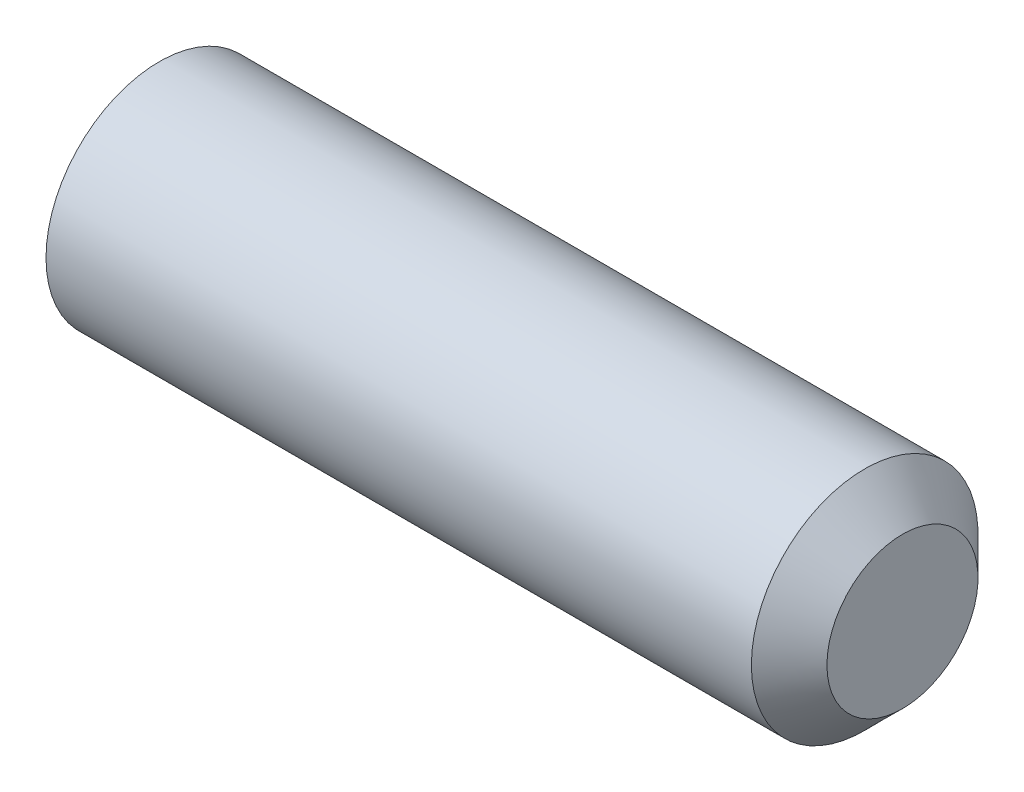
SolidWorks part; units mm, degrees
revolve "BaseBody" add sketch "BodySke" angle 360 about L5
sketch "BodySke" plane through (0, 0, 0) normal (0, 0, 1) x (1, 0, 0)
  line L0 (0, 0) -> (0, 1.2195)
  line L1 (0, 1.2195) -> (0.1619, 1.5)
  line L2 (0.1619, 1.5) -> (9.5, 1.5)
  line L3 (9.5, 1.5) -> (10, 1)
  line L4 (10, 0) -> (0, 0)
  line L5 (-12.7, 0) -> (88.9, 0) construction
  line L6 (10, 1) -> (10, 0)
  line L7 (10, 1) -> (10, 10.525) construction
  line L8 (0, -1.2195) -> (0.1619, -1.5) construction
  line L9 (0.5, 15.875) -> (0.5, -3.175) construction
  line L10 (9.5, -1.5) -> (10, -1) construction
  dimension "Diameter" = 3
  dimension "Drive_ch_ang" = 60
  dimension "Minor_dia" = 2.439
  dimension "Cup_nose_ang" = 45
  dimension "Cup_dia" = 2
  dimension "Advance" = 0.5
cosmetic thread "ThreadCosmetic" [suppressed] parameters "Thread_minor"=2.439
ref_plane "Plane1" through (0, 0, 0) normal (0, 0, 1) x (1, 0, 0)
ref_plane "Plane2" through (0, 0, 0) normal (0, 1, 0) x (1, 0, 0)
ref_plane "Plane3" through (0, 0, 0) normal (1, 0, 0) x (0, 0, -1)
sketch "Sketch2" plane through (0, 0, 0) normal (-1, 0, 0) x (0, 0, 1)
  line L0 (0.433, 0.75) -> (-0.433, 0.75)
  line L1 (-0.433, 0.75) -> (-0.866, 0)
  line L2 (0.433, 0.75) -> (0.866, 0)
  line L3 (0.433, -0.75) -> (0.866, 0)
  line L4 (0.433, -0.75) -> (-0.433, -0.75)
  line L5 (-0.433, -0.75) -> (-0.866, 0)
  dimension "Hex_size" = 1.5
  dimension "D2" = 0.75
  dimension "D3" = 0.75
extrude "Hex" cut sketch "Sketch2" against normal blind 2.1
sketch "Sketch4" plane through (0, 4.7709, -0.5249) normal (-1, 0, 0) x (0, 0, 1)
  line L0 (0.5249, -4.7709) -> (1.3124, -4.7709)
  line L1 (0.5249, -4.7709) -> (6.6732, -1.2211) construction
  line L2 (0.5249, -4.7709) -> (0.9186, -4.0889)
  line L3 (1.153, -4.6137) -> (1.2782, -4.5415)
  line L4 (0.975, -4.3054) -> (1.1002, -4.2332)
  arc A0 (1.153, -4.6137) -> (0.975, -4.3054) centre (0.5249, -4.7709) ccw
  arc A1 (1.3124, -4.7709) -> (1.2782, -4.5415) centre (0.5249, -4.7709) ccw
  arc A2 (0.9186, -4.0889) -> (1.1002, -4.2332) centre (0.5249, -4.7709) cw
  circle A3 centre (0.5249, -4.7709) radius 0.6475 construction
  circle A4 centre (0.5249, -4.7709) radius 0.7875 construction
  dimension "Spline_n_dim" = 1.295
  dimension "Spline_m_dim" = 1.575
  dimension "D1" = 30
  dimension "Spline_a_dim" = 60
  dimension "Spline_p_dim" = 0.356
  dimension "D3" = 0.178
extrude "Spline6" [suppressed] cut sketch "Sketch4" against normal blind 1.2
pattern_circular "CirPattern1" [suppressed] count 6 every 60 about axis through (-12.7, 0, 0) along (1, 0, 0)
sketch "Sketch5" plane through (0, 0.6556, 6.6316) normal (-1, 0, 0) x (0, 0, 1)
  line L0 (-6.6316, -0.6556) -> (-5.8441, -0.6556)
  line L1 (-6.6316, -0.6556) -> (-1.6115, 4.3645) construction
  line L2 (-6.6316, -0.6556) -> (-6.6316, 0.1319)
  line L3 (-6.0479, -0.3236) -> (-5.9633, -0.239)
  line L4 (-6.2996, -0.0719) -> (-6.215, 0.0127)
  line L5 (-6.2996, -0.0719) -> (-6.0479, -0.3236)
  arc A1 (-5.8441, -0.6556) -> (-5.9633, -0.239) centre (-6.6316, -0.6556) ccw
  arc A2 (-6.6316, 0.1319) -> (-6.215, 0.0127) centre (-6.6316, -0.6556) cw
  circle A3 centre (-6.6316, -0.6556) radius 0.6475 construction
  circle A4 centre (-6.6316, -0.6556) radius 0.7875 construction
  dimension "Spline_n_dim" = 1.295
  dimension "Spline_m_dim" = 1.575
  dimension "Spline_p_dim" = 0.356
  dimension "D3" = 0.178
  dimension "D1" = 45
  dimension "Spline_a_dim" = 90
extrude "Spline4" [suppressed] cut sketch "Sketch5" against normal blind 1.2
pattern_circular "CirPattern2" [suppressed] count 4 every 90 about axis through (-12.7, 0, 0) along (1, 0, 0)
sketch "ThdSchSke" plane through (0, 0, 0) normal (0, 0, 1) x (1, 0, 0)
  line L0 (0.1619, -1.2195) -> (-0.0345, -1.5)
  line L1 (0.1619, -1.2195) -> (0.3584, -1.5)
  line L2 (0.3584, -1.5) -> (0.3584, -1.875)
  line L3 (-3.175, 0) -> (5.1513, 0) construction
  line L4 (0.1619, 1.5) -> (0.1619, -1.5) construction
  line L5 (0.3584, -1.875) -> (-0.0345, -1.875)
  line L6 (-0.0345, -1.875) -> (-0.0345, -1.5)
  dimension "Thread_minor" = 2.439
  dimension "Diameter" = 3
revolve "ThreadSchematic" [suppressed] cut sketch "ThdSchSke" angle 360 about L3
pattern_linear "ThdSchPat" [suppressed]
equation "\"D2@Sketch2\" = \"Hex_size@Sketch2\" / 2"
equation "\"D3@Sketch2\" = \"Hex_size@Sketch2\" / 2"
equation "\"Thread_minor@ThreadCosmetic\" = \"Minor_dia@BodySke\""
equation "\"D1@Sketch4\" = \"Spline_a_dim@Sketch4\" / 2"
equation "\"D3@Sketch4\" = \"Spline_p_dim@Sketch4\" / 2"
equation "\"D2@CirPattern1\" = \"Spline_a_dim@Sketch4\""
equation "\"Num_teeth@CirPattern1\" = 360 / \"D2@CirPattern1\""
equation "\"Spline_a_dim@Sketch5\" = 90"
equation "\"Spline_p_dim@Sketch5\" = \"Spline_p_dim@Sketch4\""
equation "\"Spline_m_dim@Sketch5\" = \"Spline_m_dim@Sketch4\""
equation "\"Spline_n_dim@Sketch5\" = \"Spline_n_dim@Sketch4\""
equation "\"D1@Sketch5\" = \"Spline_a_dim@Sketch5\" / 2"
equation "\"D3@Sketch5\" = \"Spline_p_dim@Sketch5\" / 2"
equation "\"Key_eng@Spline4\" = \"Key_eng@Spline6\""
equation "\"Thread_minor@ThdSchSke\" = \"Thread_minor@ThreadCosmetic\""
equation "\"Diameter@ThdSchSke\" = \"Diameter@BodySke\""
equation "\"Overcut@ThdSchSke\" = \"Diameter@BodySke\" * 1.25"
equation "\"Num_threads@ThdSchPat\" = int( (\"Length@BodySke\" - ( ( ( \"Diameter@BodySke\" - \"Minor_dia@BodySke\" ) * 0.5 ) / tan( \"Drive_ch_ang@BodySke\" * 0.017453292 ) ) - ( ( ( \"Diameter@BodySke\" - \"Cup_dia@BodySke\" ) * 0.5 ) * tan( \"Cup_nose_ang@BodySke\" * 0.017453292 ) ) ) / \"Advance@BodySke\" + 0.999 )  + 1"
equation "\"Advance@ThdSchPat\" = (\"Length@BodySke\" - ( ( ( \"Diameter@BodySke\" - \"Minor_dia@BodySke\" ) * 0.5 ) / tan( \"Drive_ch_ang@BodySke\" * 0.017453292 ) ) - ( ( ( \"Diameter@BodySke\" - \"Cup_dia@BodySke\" ) * 0.5 ) * tan( \"Cup_nose_ang@BodySke\" * 0.017453292 ) ) ) /  (\"Num_threads@ThdSchPat\" - 1) 'relax it"
equation "' \"Num_threads@ThdSchPat\" = \"Num_threads@ThdSchPat\" - sgn( \"Num_threads@ThdSchPat\" - 1) '---chamfered tips only---"
